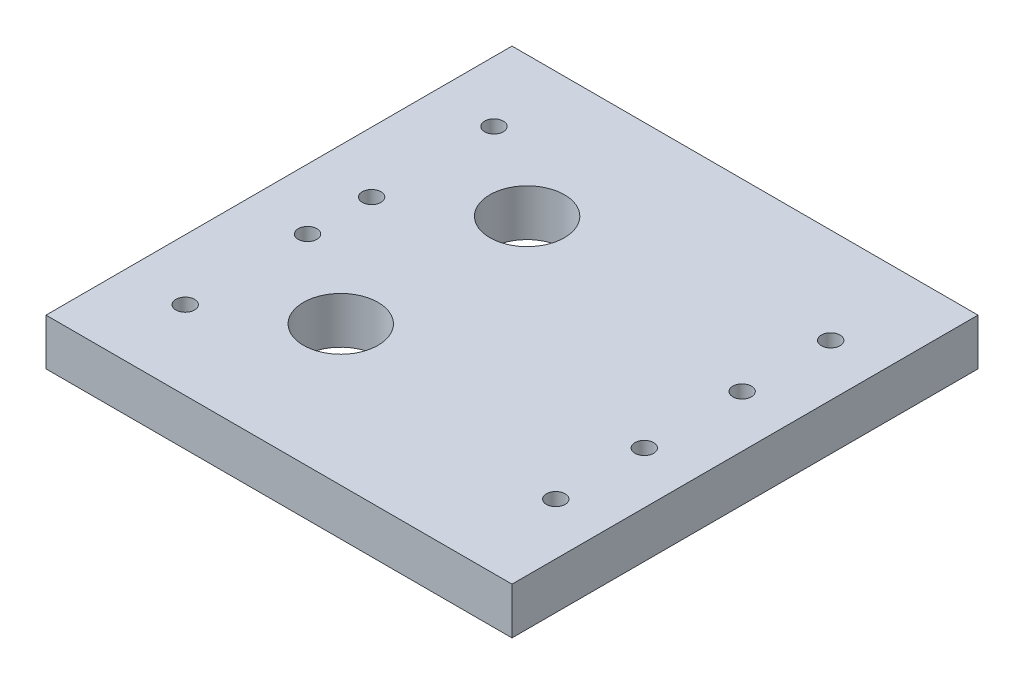
SolidWorks part; units mm, degrees
ref_plane "前视基准面" through (0, 0, 0) normal (0, 0, 1) x (1, 0, 0)
ref_plane "上视基准面" through (0, 0, 0) normal (0, 1, 0) x (1, 0, 0)
ref_plane "右视基准面" through (0, 0, 0) normal (1, 0, 0) x (0, 0, -1)
sketch "草图1" plane through (0, 0, 0) normal (0, 1, 0) x (1, 0, 0)
  line L1 (100, -100) -> (-100, -100)
  line L2 (100, -100) -> (100, 100)
  line L3 (100, 100) -> (-100, 100)
  line L4 (-100, -100) -> (-100, 100)
  line L5 (100, -100) -> (-100, 100) construction
  line L6 (100, 100) -> (-100, -100) construction
  point P0 (0, 0)
  dimension "D1" = 200
  dimension "D2" = 200
extrude "凸台-拉伸1" add sketch "草图1" along normal blind 20
sketch "草图2" plane through (0, 20, 0) normal (0, 1, 0) x (1, 0, 0)
  line L0 (-143.4563, 0) -> (137.67, 0) construction
  line L1 (0, 136.9956) -> (0, -156.175) construction
  line L2 (100, 100) -> (-100, 100) construction
  line L3 (0, -136.9956) -> (0, 156.175) construction
  circle A0 centre (-33.5, 40) radius 16
  circle A3 centre (-74, 66.25) radius 4
  circle A4 centre (-74, 13.75) radius 4
  circle A5 centre (77.78, 59) radius 4
  circle A6 centre (77.78, 21) radius 4
  circle A9 centre (77.78, -21) radius 4
  circle A10 centre (77.78, -59) radius 4
  circle A11 centre (-74, -13.75) radius 4
  circle A12 centre (-74, -66.25) radius 4
  circle A15 centre (-33.5, -40) radius 16
  dimension "D3" = 33.5
  dimension "D5" = 60
  dimension "D6" = 40.5
  dimension "D7" = 33.75
  dimension "D8" = 52.5
  dimension "D10" = 41
  dimension "D11" = 38
  dimension "D12" = 32
  dimension "D15" = 8
  dimension "D16" = 8
  dimension "D17" = 8
  dimension "D18" = 8
extrude "切除-拉伸1" cut sketch "草图2" against normal through all
